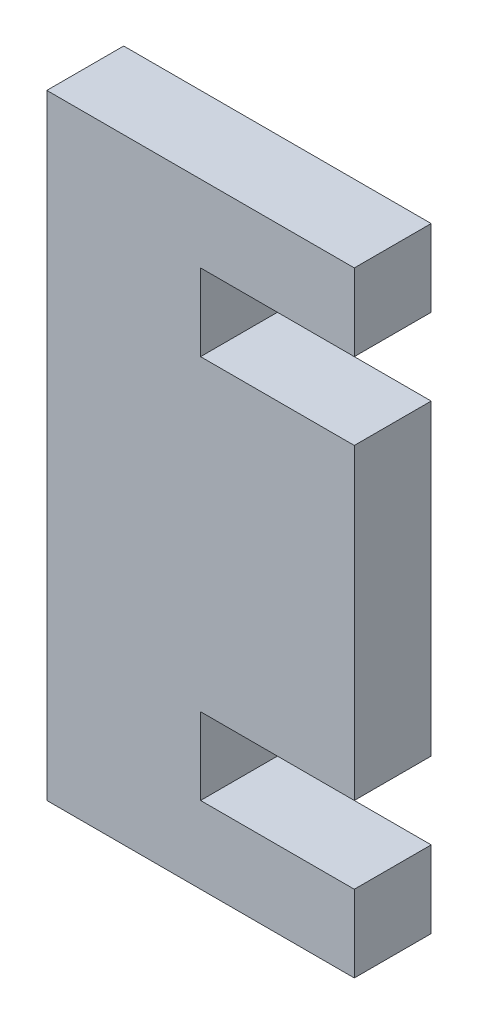
SolidWorks part; units mm, degrees
ref_plane "Front Plane" through (0, 0, 0) normal (0, 0, 1) x (1, 0, 0)
ref_plane "Top Plane" through (0, 0, 0) normal (0, 1, 0) x (1, 0, 0)
ref_plane "Right Plane" through (0, 0, 0) normal (1, 0, 0) x (0, 0, -1)
sketch "Sketch1" plane through (0, 0, 0) normal (0, 0, 1) x (1, 0, 0)
  line L0 (20, -10) -> (20, -30)
  line L1 (0, 0) -> (20, 0)
  line L2 (0, 0) -> (0, -40)
  line L3 (0, -40) -> (20, -40)
  line L4 (20, 0) -> (20, -5)
  line L5 (20, -5) -> (10, -5)
  line L7 (20, -10) -> (10, -10)
  line L8 (10, -5) -> (10, -10)
  line L9 (20, -35) -> (10, -35)
  line L11 (20, -30) -> (10, -30)
  line L12 (10, -35) -> (10, -30)
  line L13 (20, -35) -> (20, -40)
  dimension "D1" = 20
  dimension "D2" = 40
  dimension "D3" = 10
  dimension "D4" = 5
  dimension "D5" = 5
  dimension "D6" = 5
  dimension "D7" = 10
  dimension "D8" = 5
extrude "Boss-Extrude1" add sketch "Sketch1" along normal blind 5
